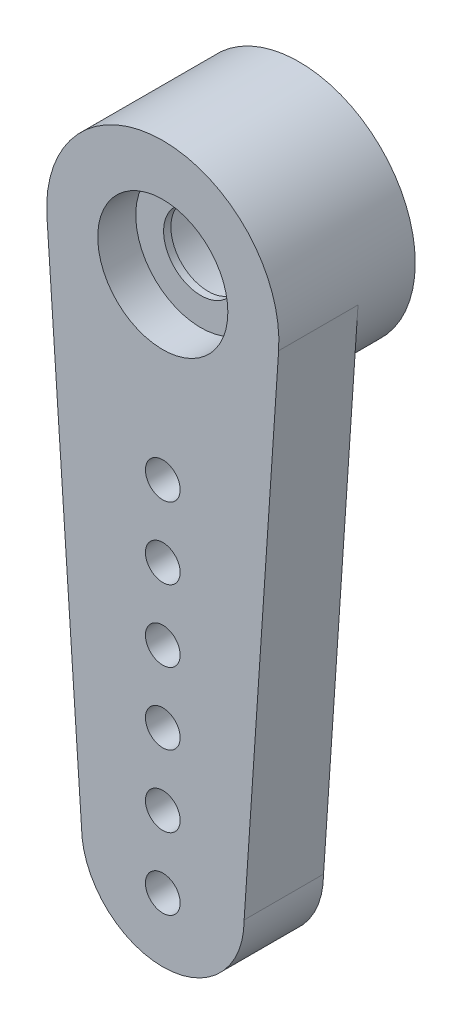
SolidWorks part; units mm, degrees
material "Nylon 6/10"
ref_plane "Front Plane" through (0, 0, 0) normal (0, 0, 1) x (1, 0, 0)
ref_plane "Top Plane" through (0, 0, 0) normal (0, 1, 0) x (1, 0, 0)
ref_plane "Right Plane" through (0, 0, 0) normal (1, 0, 0) x (0, 0, -1)
ref_plane "Plane1" through (0, 0, -7.033) normal (0, 0, 1) x (1, 0, 0)
sketch "Sketch1" plane through (0, 0, -7.033) normal (0, 0, 1) x (1, 0, 0)
  circle A0 centre (0, 0) radius 3.5687
  circle A1 centre (0, 0) radius 2
  dimension "D1" = 7.1374
  dimension "D2" = 4
extrude "Boss-Extrude1" add sketch "Sketch1" along normal blind 4.191
sketch "Sketch5" plane through (0, 0, -4.233) normal (0, 0, 1) x (1, 0, 0)
  circle A0 centre (0, 0) radius 1.143
  circle A1 centre (0, 0) radius 2 construction
  circle A2 centre (0, 0) radius 2
  dimension "D1" = 2.286
extrude "Boss-Extrude2" add sketch "Sketch5" along normal offset from surface (0.2226 mm away) 1.1684 up to face at (3.5687, 0, -2.842)
sketch "Sketch6" plane through (0, 0, -2.842) normal (0, 0, 1) x (1, 0, 0)
  line L0 (2.5, -15.9313) -> (3.56, -0.249)
  line L1 (-2.5, -15.9313) -> (-3.56, -0.249)
  line L2 (0, 0) -> (0, -15.9313) construction
  line L3 (0, -16.4647) -> (0, -14.2647) construction
  arc A0 (-2.5, -15.9313) -> (2.5, -15.9313) centre (0, -15.9313) ccw
  circle A1 centre (0, 0) radius 3.5687 construction
  circle A2 centre (0, 0) radius 3.5687 construction
  circle A3 centre (0, -14.2647) radius 0.5334
  circle A4 centre (0, -16.4647) radius 0.5334
  circle A5 centre (0, -12.0647) radius 0.5334
  circle A6 centre (0, -9.8647) radius 0.5334
  circle A7 centre (0, -7.6647) radius 0.5334
  circle A8 centre (0, -5.4647) radius 0.5334
  arc A9 (3.56, -0.249) -> (-3.56, -0.249) centre (0, 0) cw
  dimension "D1" = 5
  dimension "D2" = 22
  dimension "D4" = 1.0668
  dimension "D3" = 7.12
  dimension "D6" = 2.2
  dimension "D5" = 6
extrude "Boss-Extrude3" add sketch "Sketch6" against normal offset from surface (2.441 mm away) 1.75 up to face at (3.5687, 0, -7.033)
